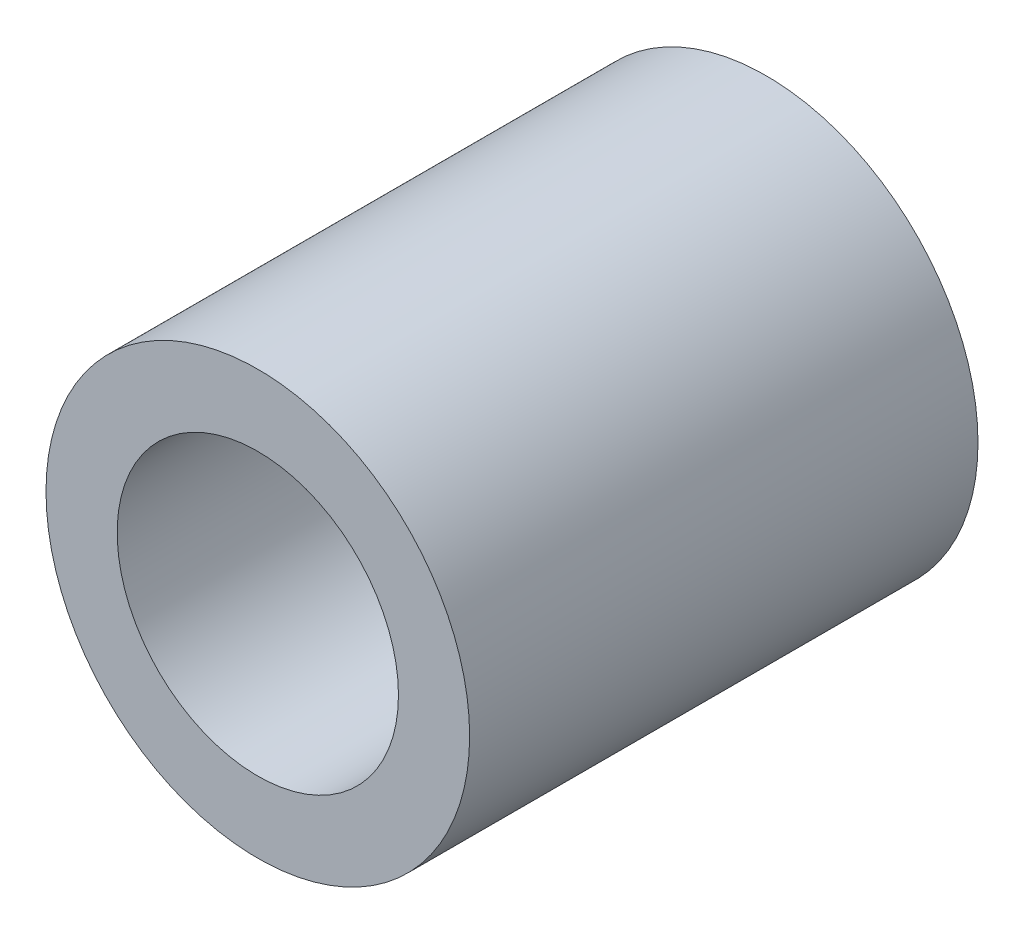
SolidWorks part; units mm, degrees
material "6061-T6 (SS)"
ref_plane "Front Plane" through (0, 0, 0) normal (0, 0, 1) x (1, 0, 0)
ref_plane "Top Plane" through (0, 0, 0) normal (0, 1, 0) x (1, 0, 0)
ref_plane "Right Plane" through (0, 0, 0) normal (1, 0, 0) x (0, 0, -1)
sketch "Sketch1" plane through (0, 0, 0) normal (1, 0, 0) x (0, 0, -1)
  line L0 (-43.4652, 0) -> (107.0331, 0) construction
  line L1 (0, 0) -> (0, 2.1082) construction
  line L2 (-3.81, 3.175) -> (3.81, 3.175)
  line L3 (-3.81, 3.175) -> (-3.81, 2.1082)
  line L4 (-3.81, 2.1082) -> (3.81, 2.1082)
  line L5 (3.81, 3.175) -> (3.81, 2.1082)
  dimension "ID" = 4.2164
  dimension "OD" = 6.35
  dimension "L" = 7.62
revolve "Revolve1" add sketch "Sketch1" angle 360 about L0
